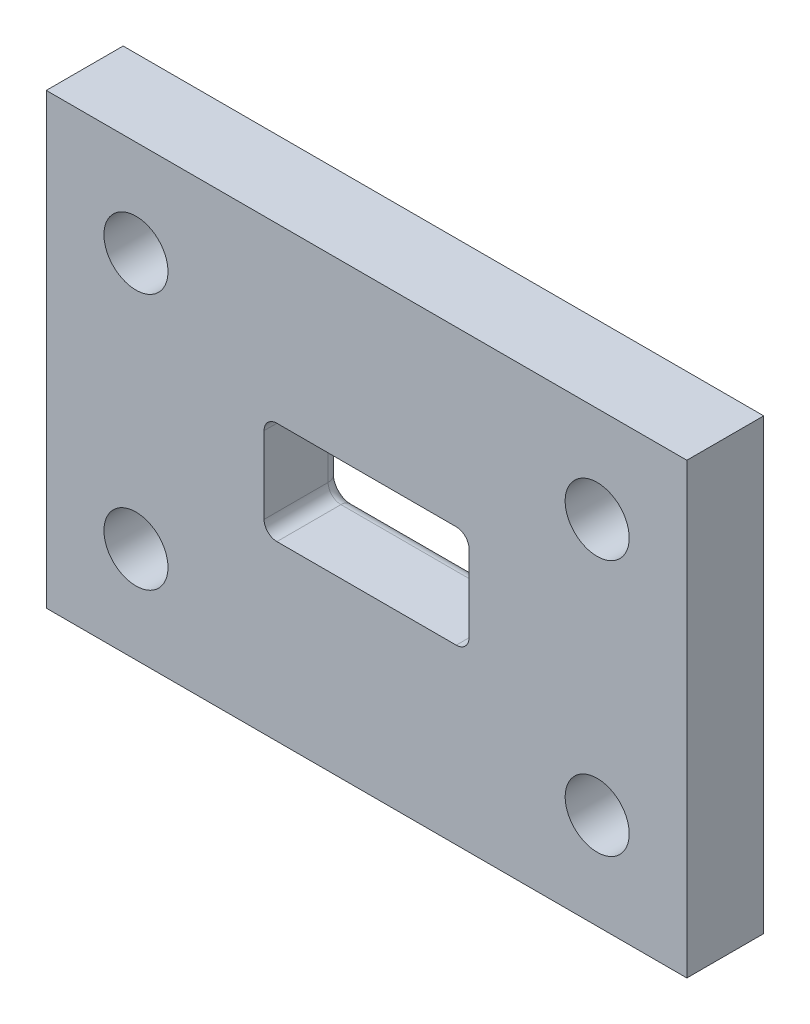
SolidWorks part; units mm, degrees
ref_plane "Ebene vorne" through (0, 0, 0) normal (0, 0, 1) x (1, 0, 0)
ref_plane "Ebene oben" through (0, 0, 0) normal (0, 1, 0) x (1, 0, 0)
ref_plane "Ebene rechts" through (0, 0, 0) normal (1, 0, 0) x (0, 0, -1)
sketch "Sketch1" plane through (0, 0, 0) normal (0, 0, 1) x (1, 0, 0)
  line L1 (-25, -17.5) -> (25, -17.5)
  line L2 (-25, -17.5) -> (-25, 17.5)
  line L3 (-25, 17.5) -> (25, 17.5)
  line L4 (25, -17.5) -> (25, 17.5)
  line L5 (-25, -17.5) -> (25, 17.5) construction
  line L6 (-25, 17.5) -> (25, -17.5) construction
  line L7 (-7, 4) -> (7, 4)
  line L8 (55, 0) -> (-55, 0) construction
  line L9 (0, -55) -> (0, 55) construction
  line L10 (-8, 3) -> (-8, -3)
  line L11 (-7, -4) -> (7, -4)
  line L12 (8, 3) -> (8, -3)
  line L13 (-8, 4) -> (8, -4) construction
  line L14 (-8, -4) -> (8, 4) construction
  circle A2 centre (18, 10) radius 2.5
  circle A6 centre (18, -10) radius 2.5
  circle A7 centre (-18, 10) radius 2.5
  circle A8 centre (-18, -10) radius 2.5
  arc A9 (7, 4) -> (8, 3) centre (7, 3) cw
  arc A10 (-8, -3) -> (-7, -4) centre (-7, -3) ccw
  arc A11 (-7, 4) -> (-8, 3) centre (-7, 3) ccw
  arc A12 (7, -4) -> (8, -3) centre (7, -3) ccw
  point P0 (0, 0)
  point P18 (0, 0)
  dimension "D3" = 5
  dimension "D5" = 18
  dimension "D6" = 8
  dimension "D8" = 1
  dimension "D1" = 50
  dimension "D2" = 35
  dimension "D4" = 10
  dimension "D7" = 16
extrude "Boss-Extrude1" add sketch "Sketch1" along normal blind 6 contours L2 L1 L4 L3 | A8 | A6 | A2 | A7 | A12 L11 A10 L10 A11 L7 A9 L12
sketch "Sketch2" plane through (0, 0, 0) normal (0, 0, 1) x (1, 0, 0)
  line L1 (-9.8, -10) -> (9.8, -10)
  line L2 (-10, -9.8) -> (-10, 9.8)
  line L3 (-9.8, 10) -> (9.8, 10)
  line L4 (10, -9.8) -> (10, 9.8)
  line L5 (-10, -10) -> (10, 10) construction
  line L6 (-10, 10) -> (10, -10) construction
  line L7 (-10.8, -11) -> (10.8, -11)
  line L8 (-11, -10.8) -> (-11, 10.8)
  line L9 (-10.8, 11) -> (10.8, 11)
  line L10 (11, -10.8) -> (11, 10.8)
  line L11 (-11, -11) -> (11, 11) construction
  line L12 (-11, 11) -> (11, -11) construction
  arc A0 (10.8, -11) -> (11, -10.8) centre (10.8, -10.8) ccw
  arc A1 (-11, 10.8) -> (-10.8, 11) centre (-10.8, 10.8) cw
  arc A2 (-10.8, -11) -> (-11, -10.8) centre (-10.8, -10.8) cw
  arc A3 (10.8, 11) -> (11, 10.8) centre (10.8, 10.8) cw
  arc A4 (9.8, -10) -> (10, -9.8) centre (9.8, -9.8) ccw
  arc A5 (-10, 9.8) -> (-9.8, 10) centre (-9.8, 9.8) cw
  arc A6 (-9.8, -10) -> (-10, -9.8) centre (-9.8, -9.8) cw
  arc A7 (9.8, 10) -> (10, 9.8) centre (9.8, 9.8) cw
  point P0 (0, 0)
  point P6 (0, 0)
  dimension "D5" = 0.2
  dimension "D1" = 20
  dimension "D2" = 20
  dimension "D3" = 22
  dimension "D4" = 22
extrude "Cut-Extrude1" cut sketch "Sketch2" along normal blind 1
fillet "Fillet3" radius 1 8 edges at (-7.7071, -3.7071, 0) (-7.7071, 3.7071, 0) (-8, 0, 0) (0, 4, 0) (7.7071, 3.7071, 0) (7.7071, -3.7071, 0) (8, 0, 0) (0, -4, 0)
